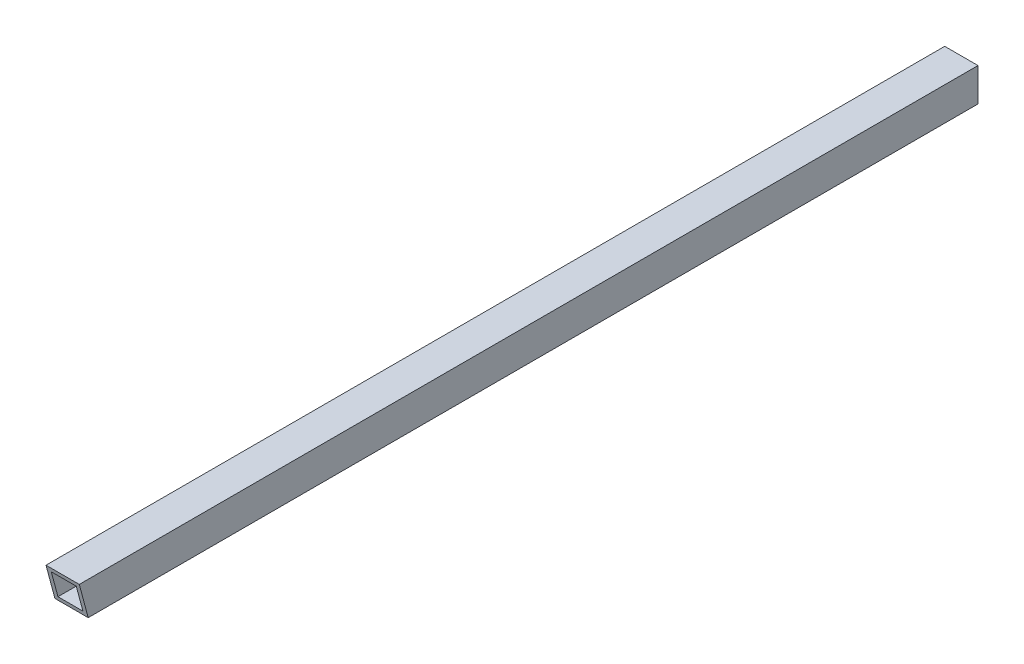
SolidWorks part; units mm, degrees
ref_plane "Front Plane" through (0, 0, 0) normal (0, 0, 1) x (1, 0, 0)
ref_plane "Top Plane" through (0, 0, 0) normal (0, 1, 0) x (1, 0, 0)
ref_plane "Right Plane" through (0, 0, 0) normal (1, 0, 0) x (0, 0, -1)
sketch "Sketch1" plane through (0, 0, 0) normal (0, 0, 1) x (1, 0, 0)
  line L1 (12.7, -12.7) -> (-12.7, -12.7)
  line L2 (12.7, -12.7) -> (12.7, 12.7)
  line L3 (12.7, 12.7) -> (-12.7, 12.7)
  line L4 (-12.7, -12.7) -> (-12.7, 12.7)
  line L5 (12.7, -12.7) -> (-12.7, 12.7) construction
  line L6 (12.7, 12.7) -> (-12.7, -12.7) construction
  line L7 (9.525, -9.525) -> (-9.525, -9.525)
  line L8 (9.525, -9.525) -> (9.525, 9.525)
  line L9 (9.525, 9.525) -> (-9.525, 9.525)
  line L10 (-9.525, -9.525) -> (-9.525, 9.525)
  line L11 (9.525, -9.525) -> (-9.525, 9.525) construction
  line L12 (9.525, 9.525) -> (-9.525, -9.525) construction
  point P0 (0, 0)
  point P6 (0, 0)
  dimension "D1" = 25.4
  dimension "D2" = 3.175
extrude "Boss-Extrude1" add sketch "Sketch1" along normal blind 685.8
ref_plane "Plane1" through (0, -170.5993, 636.6851) normal (0, -0.2588, 0.9659) x (-1, 0, 0)
sketch "Sketch2" plane through (0, 0, 685.8) normal (0, 0, 1) x (1, 0, 0)
  line L0 (-9.525, 9.525) -> (-9.525, -9.525) construction
  line L1 (-12.7, 12.7) -> (-12.7, -12.7) construction
  line L2 (-12.7, -12.7) -> (12.7, -12.7) construction
  line L3 (12.7, -12.7) -> (12.7, 12.7) construction
  line L4 (-9.525, -9.525) -> (9.525, -9.525)
  line L5 (-9.525, 9.525) -> (-9.525, -9.525)
  line L6 (9.525, 9.525) -> (-9.525, 9.525)
  line L7 (9.525, -9.525) -> (9.525, 9.525)
  line L8 (-9.525, -9.525) -> (9.525, -9.525)
  line L9 (-9.525, 9.525) -> (-9.525, -9.525)
  line L10 (9.525, 9.525) -> (-9.525, 9.525)
  line L11 (9.525, -9.525) -> (9.525, 9.525)
  line L12 (12.7, 12.7) -> (-12.7, 12.7) construction
  line L13 (-9.525, 9.525) -> (-9.525, -9.525)
  line L14 (-12.7, 12.7) -> (-12.7, -12.7)
  line L15 (-12.7, -12.7) -> (12.7, -12.7)
  line L16 (12.7, -12.7) -> (12.7, 12.7)
  line L17 (12.7, 12.7) -> (-12.7, 12.7)
  dimension "D1" = 0
sketch "Sketch3" plane through (0, -170.5993, 636.6851) normal (0, -0.2588, 0.9659) x (-1, 0, 0)
  line L0 (-12.7, -189.7654) -> (12.7, -189.7654)
  line L1 (-12.7, -189.7654) -> (12.7, -189.7654)
  line L2 (12.7, -163.4693) -> (12.7, -189.7654)
  line L3 (12.7, -163.4693) -> (12.7, -189.7654)
  line L4 (-12.7, -163.4693) -> (12.7, -163.4693)
  line L5 (-12.7, -163.4693) -> (12.7, -163.4693)
  line L6 (-12.7, -189.7654) -> (-12.7, -163.4693)
  line L7 (-12.7, -189.7654) -> (-12.7, -163.4693)
extrude "Cut-Extrude2" cut sketch "Sketch3" along normal through all
